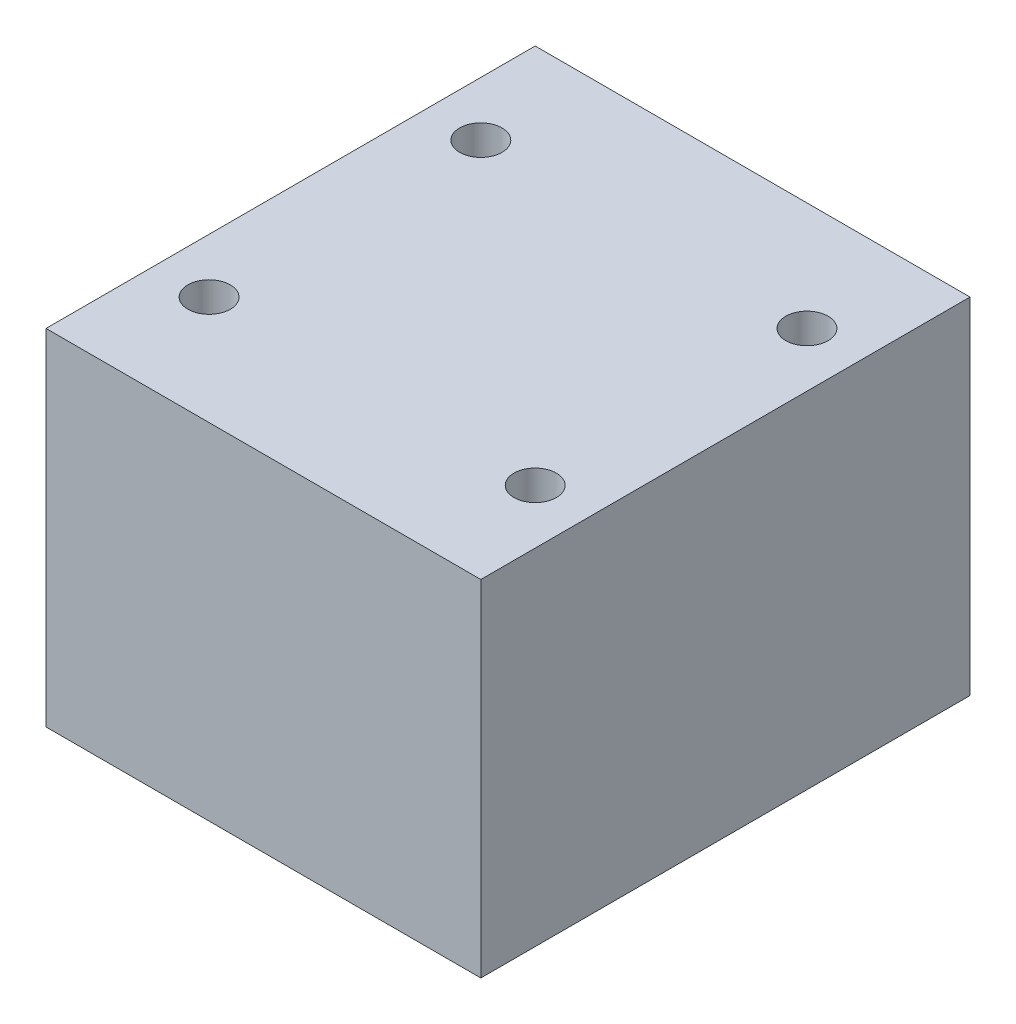
SolidWorks part; units mm, degrees
ref_plane "Front Plane" through (0, 0, 0) normal (0, 0, 1) x (1, 0, 0)
ref_plane "Top Plane" through (0, 0, 0) normal (0, 1, 0) x (1, 0, 0)
ref_plane "Right Plane" through (0, 0, 0) normal (1, 0, 0) x (0, 0, -1)
sketch "Sketch1" plane through (0, 0, 0) normal (0, 1, 0) x (1, 0, 0)
  line L1 (-10.8661, -15.7219) -> (29.1339, -15.7219)
  line L2 (-10.8661, -15.7219) -> (-10.8661, 29.2781)
  line L3 (-10.8661, 29.2781) -> (29.1339, 29.2781)
  line L4 (29.1339, -15.7219) -> (29.1339, 29.2781)
  circle A0 centre (-5.8661, 19.2781) radius 1.95
  circle A1 centre (24.1339, 19.2781) radius 1.95
  circle A2 centre (24.1339, -5.7219) radius 1.95
  circle A3 centre (-5.8661, -5.7219) radius 1.95
  dimension "D1" = 3.9
  dimension "D2" = 3.9
  dimension "D3" = 3.9
  dimension "D4" = 3.9
  dimension "D7" = 5
  dimension "D5" = 25
  dimension "D6" = 30
  dimension "D8" = 5
  dimension "D9" = 10
  dimension "D10" = 10
extrude "Boss-Extrude1" add sketch "Sketch1" along normal blind 31.75
